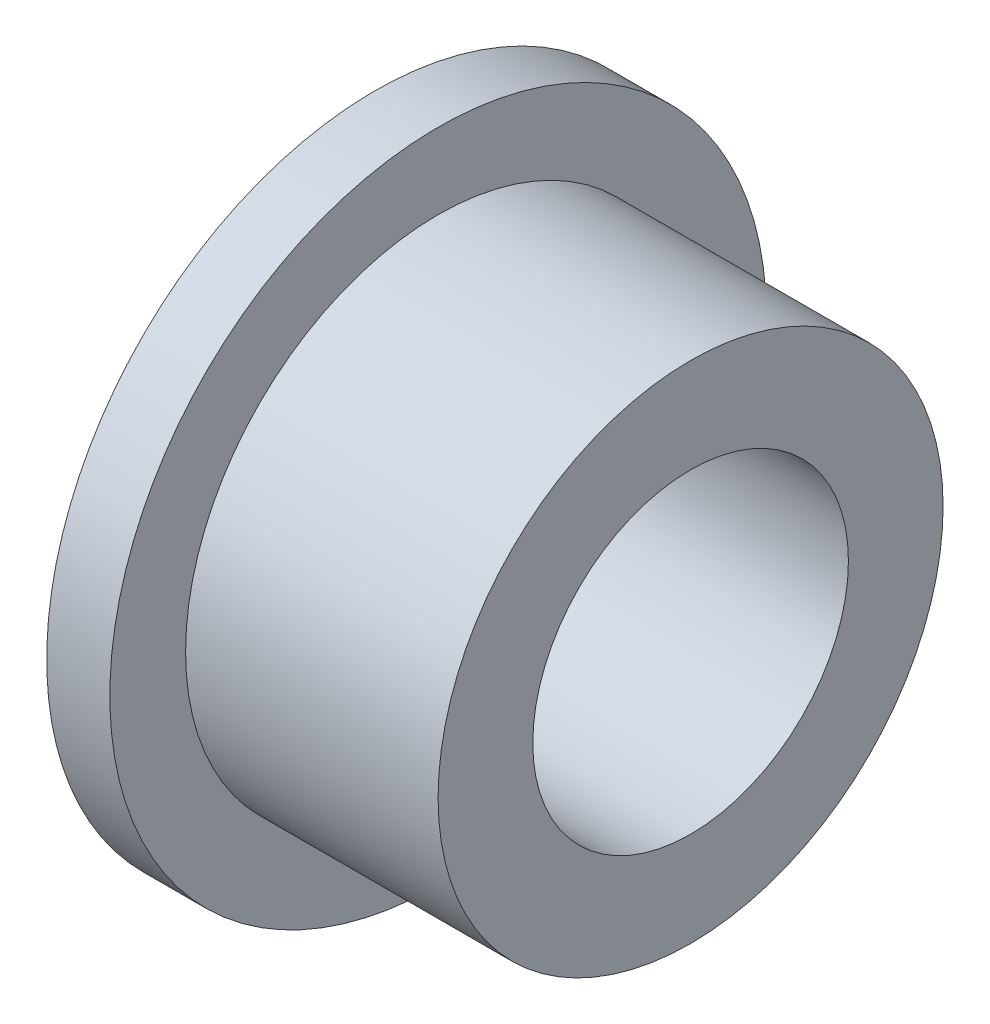
SolidWorks part; units mm, degrees
ref_plane "Front Plane" through (0, 0, 0) normal (0, 0, 1) x (1, 0, 0)
ref_plane "Top Plane" through (0, 0, 0) normal (0, 1, 0) x (1, 0, 0)
ref_plane "Right Plane" through (0, 0, 0) normal (1, 0, 0) x (0, 0, -1)
sketch "Sketch1" plane through (0, 0, 0) normal (1, 0, 0) x (0, 0, -1)
  circle A0 centre (0, 0) radius 13
  dimension "D1" = 26
extrude "Boss-Extrude1" add sketch "Sketch1" along normal blind 2.5
sketch "Sketch2" plane through (2.5, 0, 0) normal (1, 0, 0) x (0, 0, -1)
  circle A0 centre (0, 0) radius 10
  dimension "D1" = 20
extrude "Boss-Extrude2" add sketch "Sketch2" along normal blind 10
sketch "Sketch3" plane through (12.5, 0, 0) normal (1, 0, 0) x (0, 0, -1)
  circle A0 centre (0, 0) radius 6.25
  dimension "D1" = 12.5
extrude "Cut-Extrude1" cut sketch "Sketch3" against normal blind 21
